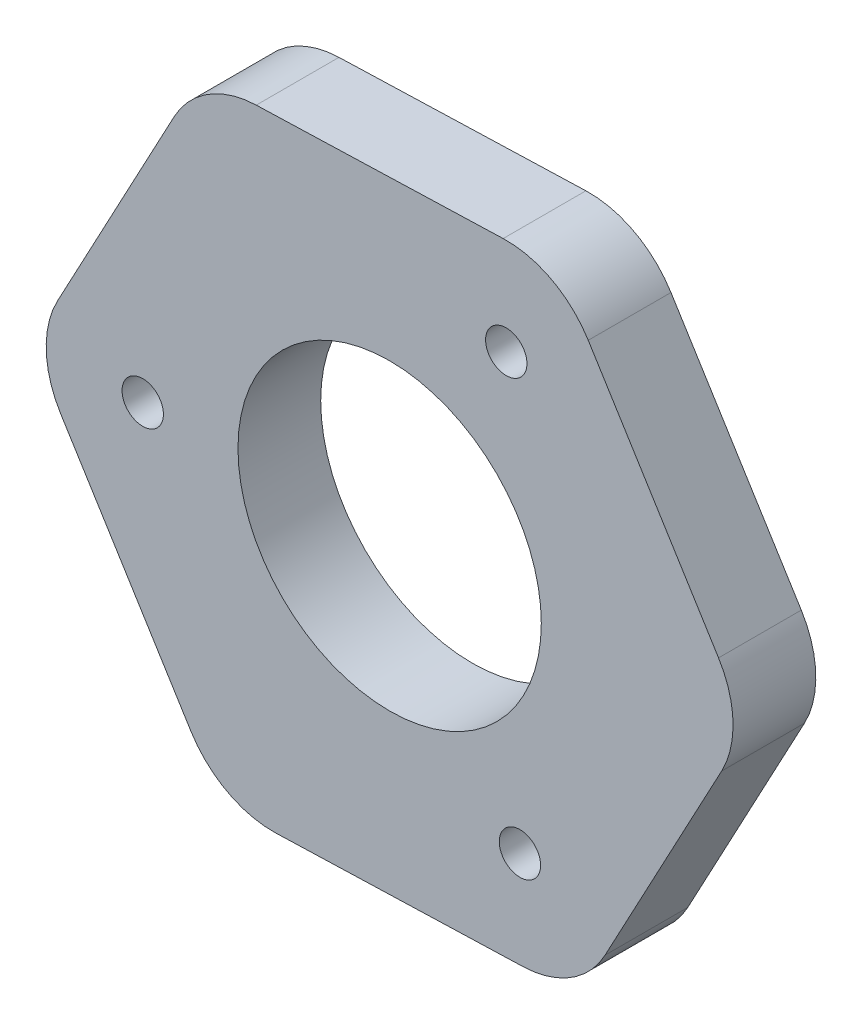
SolidWorks part; units mm, degrees
ref_plane "Front Plane" through (0, 0, 0) normal (0, 0, 1) x (1, 0, 0)
ref_plane "Top Plane" through (0, 0, 0) normal (0, 1, 0) x (1, 0, 0)
ref_plane "Right Plane" through (0, 0, 0) normal (1, 0, 0) x (0, 0, -1)
sketch "Sketch1" plane through (0, 0, 0) normal (0, 0, 1) x (1, 0, 0)
  line L6 (56.5415, 380.9628) -> (38.6336, 380.3894)
  line L7 (72.163, 362.4365) -> (62.7126, 377.6585)
  line L8 (63.9296, 339.6447) -> (72.387, 355.4401)
  line L9 (40.0746, 335.3792) -> (57.9825, 335.9525)
  line L10 (24.453, 353.9055) -> (33.9035, 338.6834)
  line L11 (32.6865, 376.6973) -> (24.229, 360.9019)
  circle A10 centre (57.7585, 342.9489) radius 1.5
  circle A11 centre (56.7655, 373.9664) radius 1.5
  circle A12 centre (30.4001, 357.5976) radius 1.5
  circle A13 centre (48.308, 358.171) radius 11
  arc A14 (38.6336, 380.3894) -> (32.6865, 376.6973) centre (38.8576, 373.393) ccw
  arc A15 (62.7126, 377.6585) -> (56.5415, 380.9628) centre (56.7655, 373.9664) ccw
  arc A16 (72.387, 355.4401) -> (72.163, 362.4365) centre (66.216, 358.7443) ccw
  arc A17 (57.9825, 335.9525) -> (63.9296, 339.6447) centre (57.7585, 342.9489) ccw
  arc A18 (33.9035, 338.6834) -> (40.0746, 335.3792) centre (39.8506, 342.3756) ccw
  arc A19 (24.229, 360.9019) -> (24.453, 353.9055) centre (30.4001, 357.5976) ccw
  point P1 (0, 0)
  point P3 (0, 0)
  point P7 (26.1755, 351.131)
  point P22 (56.8846, 373.0847)
  point P25 (48.3799, 357.6914)
  dimension "D11" = 22
  dimension "D18" = 3
  dimension "D19" = 7
  dimension "D1" = 335.3792
  dimension "D2" = 40.0746
  dimension "D3" = 333.9251
  dimension "D4" = 17.9171
  dimension "D5" = 60
  dimension "D6" = 60
  dimension "D7" = 60
  dimension "D8" = 60
  dimension "D9" = 60
  dimension "D10" = 60
  dimension "D12" = 7
  dimension "D13" = 7
  dimension "D14" = 7
  dimension "D15" = 7
  dimension "D16" = 7
  dimension "D17" = 7
  dimension "D20" = 22.5167
  dimension "D21" = 22.5167
extrude "Boss-Extrude1" add sketch "Sketch1" along normal blind 6 separate body
